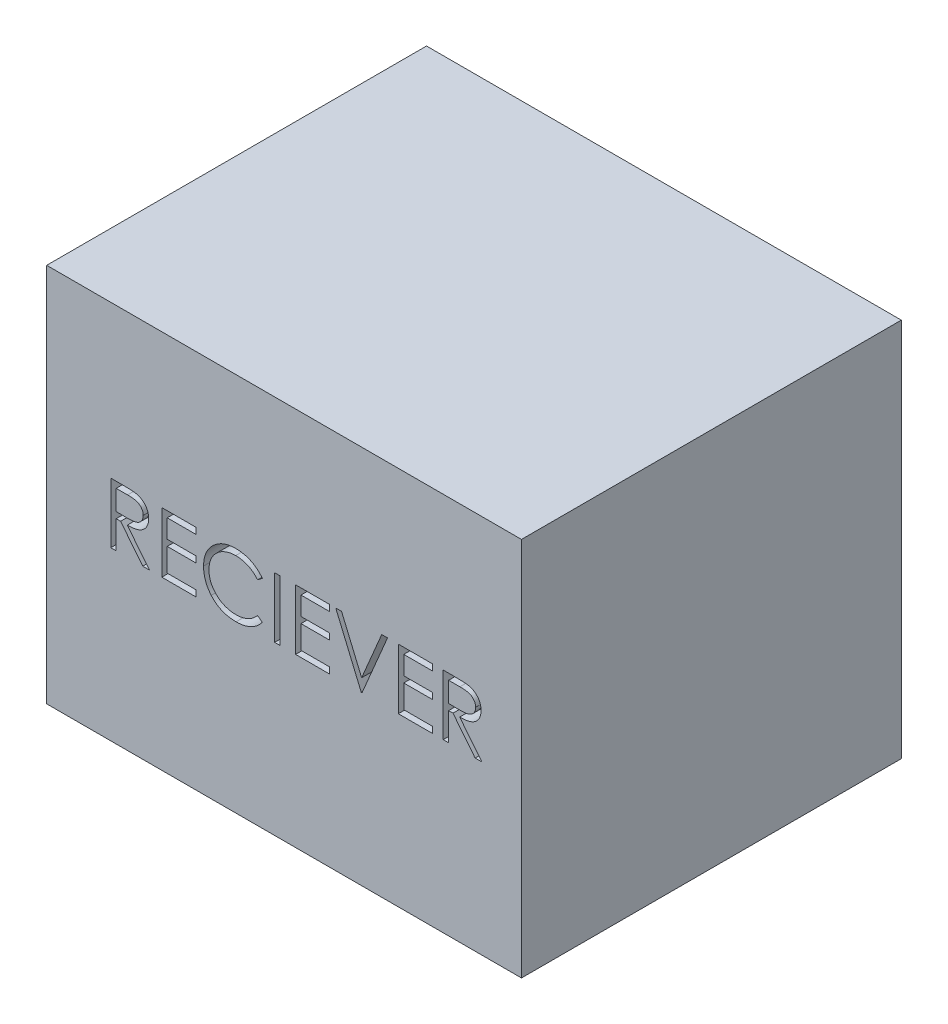
SolidWorks part; units mm, degrees
ref_plane "Front Plane" through (0, 0, 0) normal (0, 0, 1) x (1, 0, 0)
ref_plane "Top Plane" through (0, 0, 0) normal (0, 1, 0) x (1, 0, 0)
ref_plane "Right Plane" through (0, 0, 0) normal (1, 0, 0) x (0, 0, -1)
sketch "Sketch1" plane through (0, 0, 0) normal (1, 0, 0) x (0, 0, -1)
  line L1 (-20, 20) -> (20, 20)
  line L2 (-20, 20) -> (-20, -20)
  line L3 (-20, -20) -> (20, -20)
  line L4 (20, 20) -> (20, -20)
  point P4 (0, 0)
  point P5 (0, 20)
  point P6 (-20, 0)
  dimension "D1" = 40
extrude "Boss-Extrude1" add sketch "Sketch1" along normal mid plane 50 contours L2 L3 L4 L1
sketch "Sketch2" plane through (0, 0, 20) normal (0, 0, 1) x (1, 0, 0)
  text T0 "RECIEVER" font "Century Gothic" height in points 24
extrude "Cut-Extrude1" cut sketch "Sketch2" against normal blind 10
